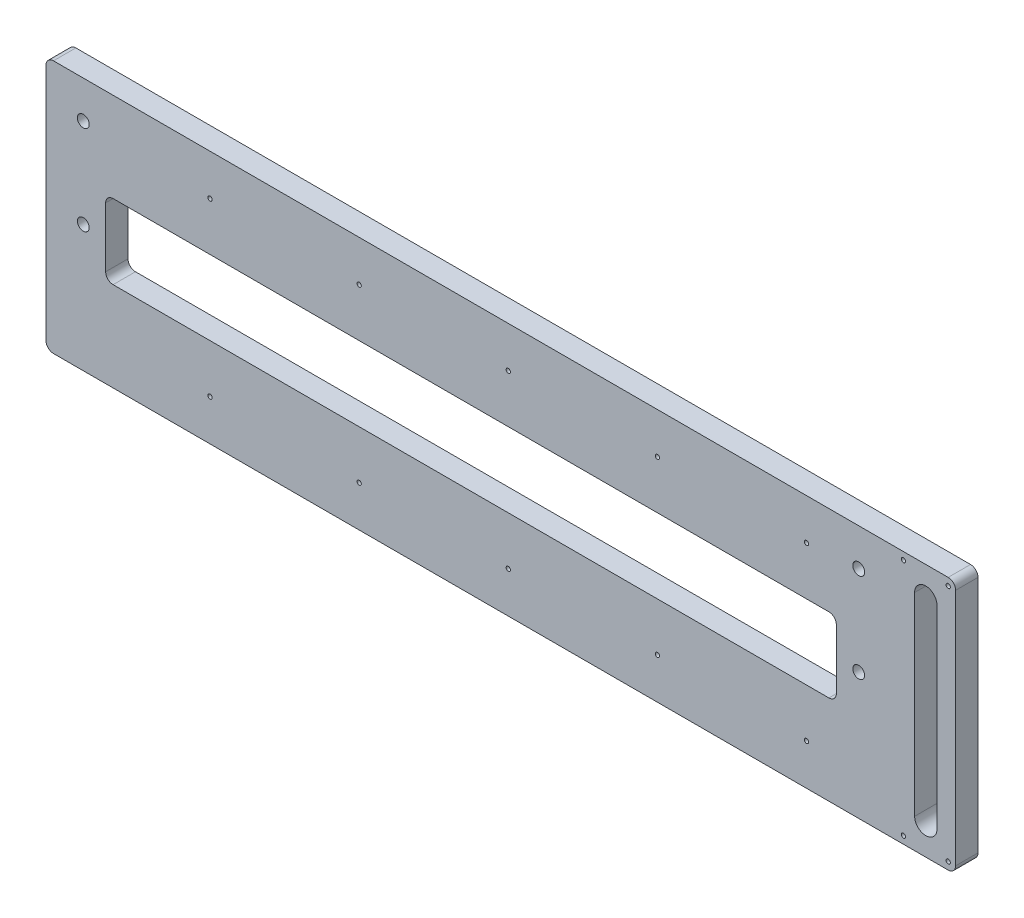
SolidWorks part; units mm, degrees
ref_plane "Front Plane" through (0, 0, 0) normal (0, 0, 1) x (1, 0, 0)
ref_plane "Top Plane" through (0, 0, 0) normal (0, 1, 0) x (1, 0, 0)
ref_plane "Right Plane" through (0, 0, 0) normal (1, 0, 0) x (0, 0, -1)
sketch "Sketch2" plane through (0, 0, 0) normal (0, 0, 1) x (1, 0, 0)
  line L0 (330.2, 107.95) -> (330.2, -107.95)
  line L1 (-393.7, -107.95) -> (330.2, -107.95)
  line L2 (-393.7, -107.95) -> (-393.7, 107.95)
  line L3 (-393.7, 107.95) -> (330.2, 107.95)
  line L5 (-393.7, -107.95) -> (393.7, 107.95) construction
  line L6 (-393.7, 107.95) -> (393.7, -107.95) construction
  point P0 (0, 0)
  dimension "D1" = 787.4
  dimension "D2" = 215.9
extrude "Boss-Extrude1" add sketch "Sketch2" along normal blind 19.05
sketch "Sketch13" plane through (0, 0, 19.05) normal (0, 0, 1) x (1, 0, 0)
  line L1 (-336.55, -31.75) -> (273.05, -31.75)
  line L2 (-342.9, -25.4) -> (-342.9, 25.4)
  line L3 (-336.55, 31.75) -> (273.05, 31.75)
  line L4 (279.4, -25.4) -> (279.4, 25.4)
  line L5 (-342.9, -31.75) -> (279.4, 31.75) construction
  line L6 (-342.9, 31.75) -> (279.4, -31.75) construction
  line L7 (-393.7, 107.95) -> (-393.7, -107.95) construction
  line L9 (330.2, -107.95) -> (330.2, 107.95) construction
  arc A0 (273.05, 31.75) -> (279.4, 25.4) centre (273.05, 25.4) cw
  arc A1 (273.05, -31.75) -> (279.4, -25.4) centre (273.05, -25.4) ccw
  arc A2 (-336.55, -31.75) -> (-342.9, -25.4) centre (-336.55, -25.4) cw
  arc A3 (-342.9, 25.4) -> (-336.55, 31.75) centre (-336.55, 25.4) cw
  point P19 (279.4, 0)
  dimension "D3" = 6.35
  dimension "D1" = 63.5
  dimension "D2" = 50.8
  dimension "D4" = 50.8
extrude "Cut-Extrude3" cut sketch "Sketch13" against normal through all
hole_wizard "#27 (0.144) Diameter Hole1" positions "Sketch14" profile "Sketch15" hole size "#27" standard "ANSI Inch" end condition through all
sketch "Sketch14" plane through (0, 0, 0) normal (0, 0, -1) x (-1, 0, 0)
  line L1 (-254, -73.025) -> (254, -73.025) construction
  line L2 (-254, -73.025) -> (-254, 73.025) construction
  line L3 (-254, 73.025) -> (254, 73.025) construction
  line L4 (254, -73.025) -> (254, 73.025) construction
  line L5 (-254, -73.025) -> (254, 73.025) construction
  line L6 (-254, 73.025) -> (254, -73.025) construction
  point P1 (0, 0)
  point P22 (-254, 73.025)
  point P36 (-127, 73.025)
  point P37 (0, 73.025)
  point P38 (127, 73.025)
  point P39 (254, 73.025)
  point P40 (-127, -73.025)
  point P41 (0, -73.025)
  point P42 (127, -73.025)
  point P43 (254, -73.025)
  point P44 (-254, -73.025)
  dimension "D1" = 146.05
  dimension "D2" = 508
  dimension "D3" = 5
  dimension "D4" = 2
sketch "Sketch15" plane through (0, 0, 0) normal (1, 0, 0) x (0, 1, 0)
  line L0 (0, 0) -> (0, 19.05)
  line L1 (0, 19.05) -> (1.8288, 19.05)
  line L2 (1.8288, 19.05) -> (1.8288, 0)
  line L5 (1.8288, 0) -> (0, 0)
  line L11 (0, -6.35) -> (0, 107.95) construction
  dimension "Thru Hole Dia." = 3.6576
  dimension "Thru Hole Depth" = 19.05
hole_wizard "3/8 Clearance Hole1" positions "Sketch18" profile "Sketch19" hole size "3/8" standard "ANSI Inch" end condition through all
sketch "Sketch18" plane through (0, 0, 0) normal (0, 0, -1) x (-1, 0, 0)
  line L0 (-330.2, -107.95) -> (-330.2, 107.95) construction
  line L1 (-330.2, 107.95) -> (393.7, 107.95) construction
  line L2 (393.7, 107.95) -> (393.7, -107.95) construction
  line L5 (-298.45, 76.2) -> (361.95, 76.2) construction
  line L6 (-298.45, 76.2) -> (-298.45, 0) construction
  line L7 (-298.45, 0) -> (361.95, 0) construction
  line L8 (361.95, 76.2) -> (361.95, 0) construction
  point P0 (-298.45, 76.2)
  point P2 (361.95, 76.2)
  point P73 (361.95, 0)
  point P128 (-298.45, 0)
  dimension "D1" = 31.75
  dimension "D2" = 31.75
  dimension "D3" = 31.75
  dimension "D4" = 31.75
  dimension "D5" = 76.2
sketch "Sketch19" plane through (298.45, 76.2, 0) normal (1, 0, 0) x (0, 1, 0)
  line L0 (0, 0) -> (0, 19.05)
  line L1 (0, 19.05) -> (5.0419, 19.05)
  line L2 (5.0419, 19.05) -> (5.0419, 0)
  line L5 (5.0419, 0) -> (0, 0)
  line L11 (0, -6.35) -> (0, 107.95) construction
  dimension "Thru Hole Dia." = 10.0838
  dimension "Thru Hole Depth" = 19.05
sketch "Sketch22" plane through (330.2, 0, 0) normal (1, 0, 0) x (0, 0, -1)
  line L1 (-19.05, 107.95) -> (0, 107.95)
  line L2 (-19.05, 107.95) -> (-19.05, -107.95)
  line L3 (-19.05, -107.95) -> (0, -107.95)
  line L4 (0, 107.95) -> (0, -107.95)
extrude "Boss-Extrude2" add sketch "Sketch22" along normal blind 50.8
fillet "Fillet1" radius 6.35 4 edges at (-393.7, -107.95, 9.525) (-393.7, 107.95, 9.525) (381, -107.95, 9.525) (381, 107.95, 9.525)
hole_wizard "#6 Clearance Hole1" positions "Sketch23" profile "Sketch24" hole size "#6" standard "ANSI Inch" end condition through all
sketch "Sketch23" plane through (0, 0, 19.05) normal (0, 0, 1) x (1, 0, 0)
  line L0 (355.6, 107.95) -> (355.6, -107.95) construction
  line L1 (374.65, 107.95) -> (-387.35, 107.95) construction
  line L2 (-387.35, -107.95) -> (374.65, -107.95) construction
  line L4 (381, 101.6) -> (381, -101.6) construction
  line L6 (374.65, -101.6) -> (336.55, -101.6) construction
  line L7 (374.65, -101.6) -> (374.65, 101.6) construction
  line L8 (374.65, 101.6) -> (336.55, 101.6) construction
  line L9 (336.55, -101.6) -> (336.55, 101.6) construction
  line L10 (374.65, -101.6) -> (336.55, 101.6) construction
  line L11 (374.65, 101.6) -> (336.55, -101.6) construction
  point P9 (355.6, 0)
  point P10 (336.55, 101.6)
  point P55 (374.65, -101.6)
  point P56 (374.65, 101.6)
  point P57 (336.55, -101.6)
  dimension "D1" = 25.4
  dimension "D2" = 203.2
  dimension "D3" = 38.1
sketch "Sketch24" plane through (336.55, -101.6, 19.05) normal (1, 0, 0) x (0, -1, 0)
  line L0 (0, 0) -> (0, 19.05)
  line L1 (0, 19.05) -> (1.8288, 19.05)
  line L2 (1.8288, 19.05) -> (1.8288, 0)
  line L5 (1.8288, 0) -> (0, 0)
  line L11 (0, -6.35) -> (0, 107.95) construction
  dimension "Thru Hole Dia." = 3.6576
  dimension "Thru Hole Depth" = 19.05
sketch "Sketch25" plane through (0, 0, 19.05) normal (0, 0, 1) x (1, 0, 0)
  line L0 (336.55, 101.6) -> (374.65, -101.6) construction
  line L1 (355.6, -82.55) -> (355.6, 82.55) construction
  line L2 (346.075, -82.55) -> (346.075, 82.55)
  line L3 (365.125, -82.55) -> (365.125, 82.55)
  arc A0 (346.075, -82.55) -> (365.125, -82.55) centre (355.6, -82.55) ccw
  arc A1 (365.125, 82.55) -> (346.075, 82.55) centre (355.6, 82.55) ccw
  point P6 (355.6, 0)
  dimension "D1" = 19.05
  dimension "D2" = 165.1
extrude "Cut-Extrude4" cut sketch "Sketch25" against normal blind 76.2
